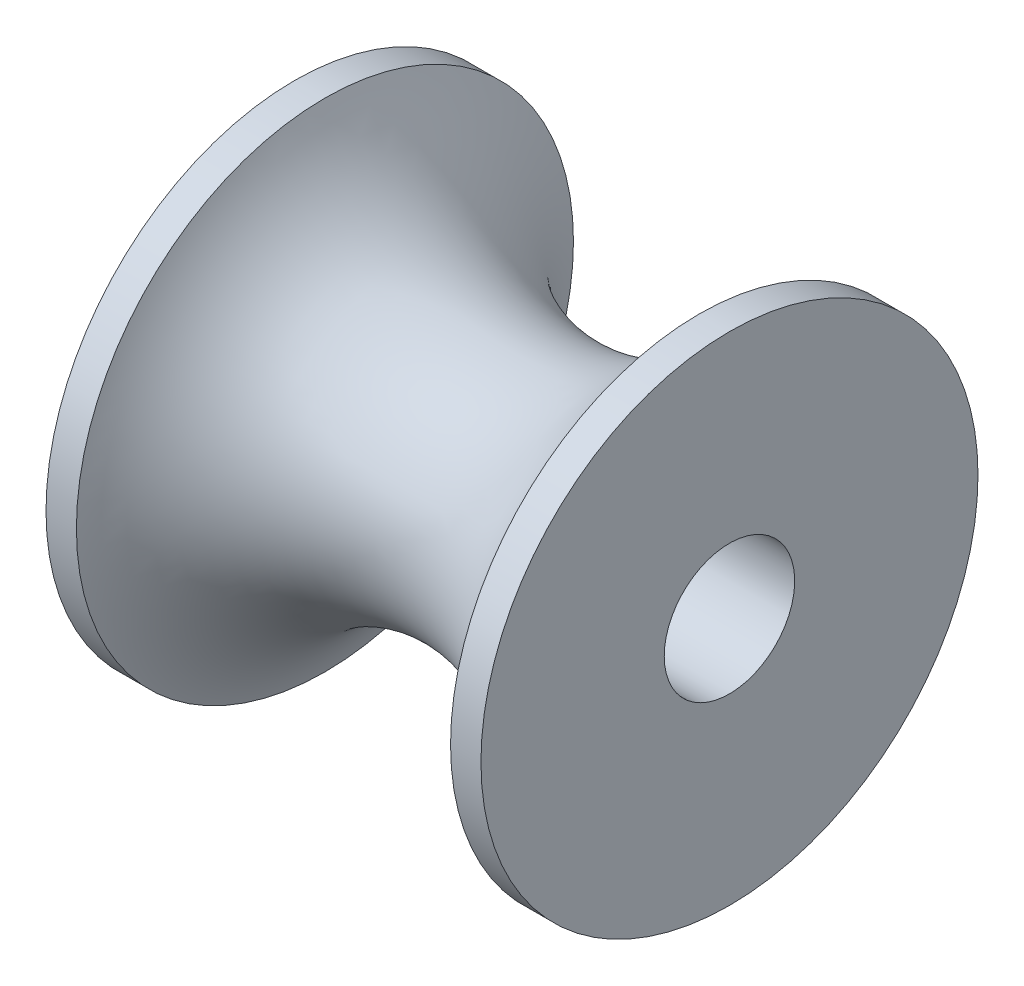
SolidWorks part; units mm, degrees
ref_plane "Front Plane" through (0, 0, 0) normal (0, 0, 1) x (1, 0, 0)
ref_plane "Top Plane" through (0, 0, 0) normal (0, 1, 0) x (1, 0, 0)
ref_plane "Right Plane" through (0, 0, 0) normal (1, 0, 0) x (0, 0, -1)
sketch "Sketch2" plane through (0, 0, 0) normal (0, 1, 0) x (1, 0, 0)
  line L0 (7, 3.9479) -> (7, 10.4479) construction
  line L1 (0, 0) -> (14, 0)
  line L2 (0, 0) -> (0, 8)
  line L3 (0, 8) -> (0.9786, 8)
  line L4 (14, 0) -> (14, 8)
  line L5 (13.0214, 8) -> (14, 8)
  arc A1 (0.9786, 8) -> (13.0214, 8) centre (7, 10.4479) ccw
  circle A2 centre (7, 10.4479) radius 6.5 construction
  dimension "D1" = 13
  dimension "D2" = 14
  dimension "D3" = 8
  dimension "D4" = 6.5
revolve "Revolve2" add sketch "Sketch2" angle 360 about L1
sketch "Sketch3" plane through (0, 0, 0) normal (-1, 0, 0) x (0, 0, 1)
  circle A0 centre (0, 0) radius 2.1
  dimension "D1" = 4.2
extrude "Cut-Extrude1" cut sketch "Sketch3" against normal through all
